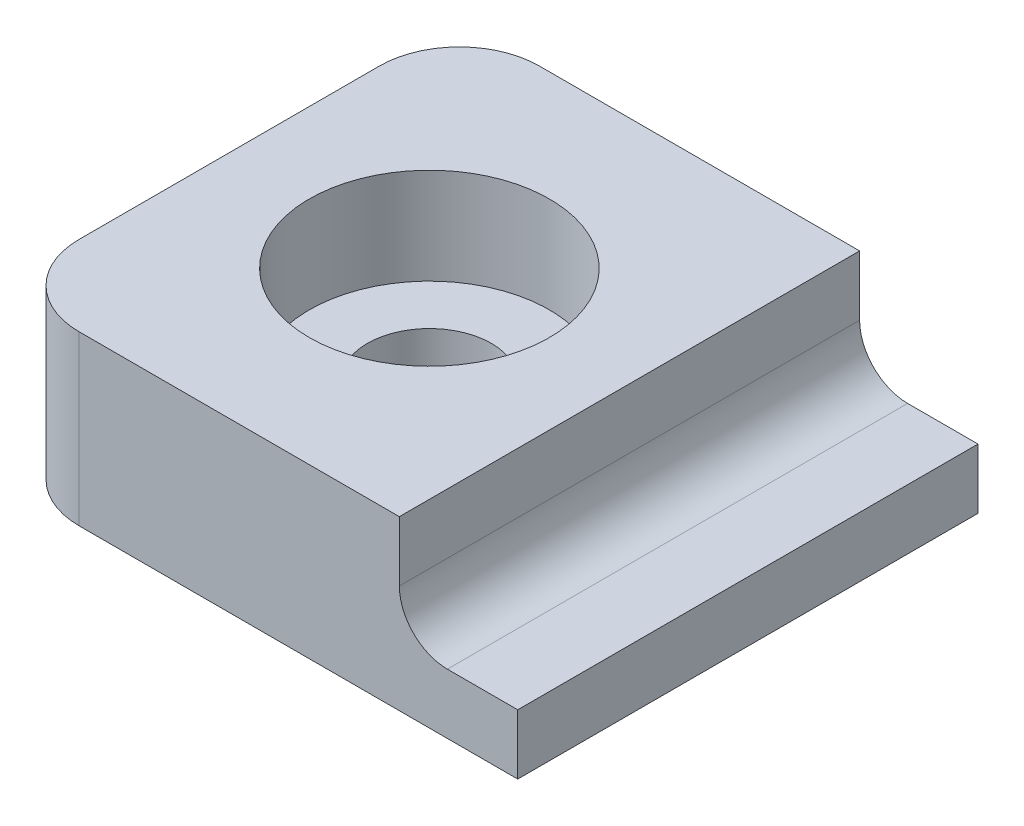
SolidWorks part; units mm, degrees
ref_plane "Front Plane" through (0, 0, 0) normal (0, 0, 1) x (1, 0, 0)
ref_plane "Top Plane" through (0, 0, 0) normal (0, 1, 0) x (1, 0, 0)
ref_plane "Right Plane" through (0, 0, 0) normal (1, 0, 0) x (0, 0, -1)
sketch "Sketch1" plane through (0, 0, 0) normal (0, 1, 0) x (1, 0, 0)
  line L0 (0, 0) -> (0, 4.9523) construction
  line L1 (0, 4.9523) -> (0, 0) construction
  line L2 (0, 0) -> (2.8355, 0) construction
  circle A0 centre (0, 0) radius 13.97
  circle A2 centre (0, 9.5) radius 1.275
  circle A3 centre (9.5, 0) radius 1.275
  circle A4 centre (0, -9.5) radius 1.275
  circle A5 centre (-9.5, 0) radius 1.275
  dimension "D2" = 27.94
  dimension "D3" = 2.55
extrude "Boss-Extrude1" add sketch "Sketch1" along normal blind 3.048
sketch "Sketch2" plane through (0, 3.048, 0) normal (0, 1, 0) x (1, 0, 0)
  line L1 (-96.52, -14.605) -> (96.52, -14.605)
  line L2 (-101.6, -9.525) -> (-101.6, 9.525)
  line L3 (-96.52, 14.605) -> (96.52, 14.605)
  line L4 (101.6, -9.525) -> (101.6, 9.525)
  line L5 (-101.6, -14.605) -> (101.6, 14.605) construction
  line L6 (-101.6, 14.605) -> (101.6, -14.605) construction
  circle A0 centre (-88.9, 0) radius 7.62
  circle A1 centre (88.9, 0) radius 7.62
  arc A3 (96.52, 14.605) -> (101.6, 9.525) centre (96.52, 9.525) cw
  arc A4 (96.52, -14.605) -> (101.6, -9.525) centre (96.52, -9.525) ccw
  arc A5 (-96.52, -14.605) -> (-101.6, -9.525) centre (-96.52, -9.525) cw
  arc A6 (-101.6, 9.525) -> (-96.52, 14.605) centre (-96.52, 9.525) cw
  circle A7 centre (9.5, 0) radius 1.275 construction
  circle A8 centre (0, 9.5) radius 1.275 construction
  circle A9 centre (-9.5, 0) radius 1.275 construction
  circle A10 centre (0, -9.5) radius 1.275 construction
  circle A11 centre (9.5, 0) radius 1.275
  circle A12 centre (0, 9.5) radius 1.275
  circle A13 centre (-9.5, 0) radius 1.275
  circle A14 centre (0, -9.5) radius 1.275
  point P0 (0, 0)
  dimension "D2" = 15.24
  dimension "D3" = 15.24
  dimension "D8" = 5.08
  dimension "D1" = 29.21
  dimension "D4" = 88.9
  dimension "D6" = 12.7
  dimension "D7" = 12.7
extrude "Boss-Extrude2" add sketch "Sketch2" along normal blind 7.62 and the other way through all
sketch "Sketch5" plane through (0, 0, -14.605) normal (0, 0, -1) x (-1, 0, 0)
  line L0 (-101.6, 0) -> (-101.6, 10.668)
  line L1 (-101.6, 10.668) -> (-76.2, 10.668)
  line L2 (-96.52, 10.668) -> (96.52, 10.668) construction
  line L3 (-76.2, 10.668) -> (-76.2, 3.81)
  line L4 (-76.2, 3.81) -> (76.2, 3.81)
  line L5 (0, 3.81) -> (0, 0)
  line L6 (101.6, 0) -> (-101.6, 0)
  line L7 (76.2, 10.668) -> (76.2, 3.81)
  line L8 (101.6, 10.668) -> (76.2, 10.668)
  line L9 (101.6, 0) -> (101.6, 10.668)
  line M8 (96.52, 10.668) -> (-96.52, 10.668)
  dimension "D1" = 25.4
  dimension "D2" = 3.81
extrude "Cut-Extrude2" cut sketch "Sketch5" against normal through all contours L7 L3 L4 M8
sketch "Sketch6" plane through (0, 0, 0) normal (0, -1, 0) x (1, 0, 0)
  circle A0 centre (-88.9, 0) radius 8.89
  circle A1 centre (-88.9, 0) radius 3.937
  circle A2 centre (88.9, 0) radius 8.89
  circle A3 centre (88.9, 0) radius 3.937
  dimension "D1" = 7.874
  dimension "D2" = 7.874
extrude "Boss-Extrude3" add sketch "Sketch6" against normal blind 4.572
fillet "Fillet2" radius 3.048 2 edges at (76.2, 3.81, 0) (-76.2, 3.81, 0)
sketch "Sketch8" plane through (0, 0, 14.605) normal (0, 0, 1) x (1, 0, 0)
  line L1 (-68.6869, 12.1384) -> (107.5845, 12.1384)
  line L2 (-68.6869, 12.1384) -> (-68.6869, -14.2219)
  line L3 (-68.6869, -14.2219) -> (107.5845, -14.2219)
  line L4 (107.5845, 12.1384) -> (107.5845, -14.2219)
extrude "Cut-Extrude3" cut sketch "Sketch8" against normal through all
